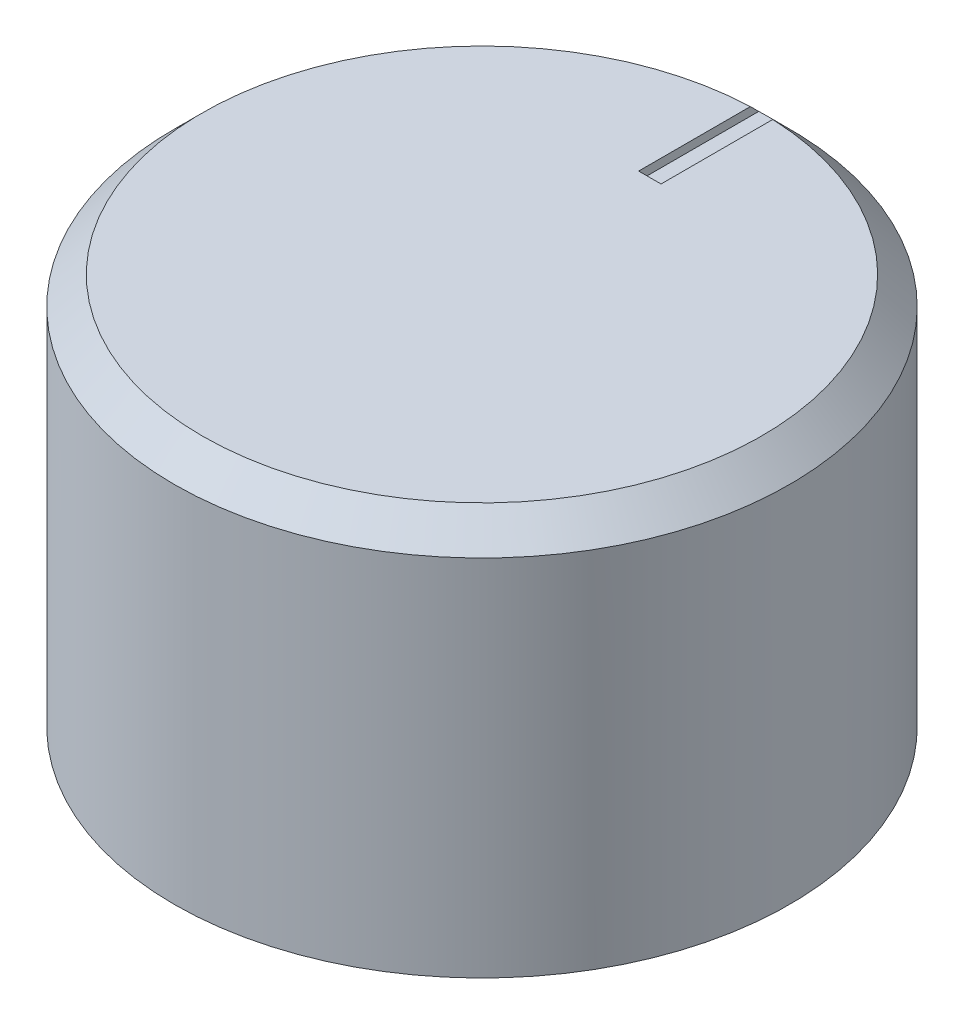
SolidWorks part; units mm, degrees
ref_plane "Front Plane" through (0, 0, 0) normal (0, 0, 1) x (1, 0, 0)
ref_plane "Top Plane" through (0, 0, 0) normal (0, 1, 0) x (1, 0, 0)
ref_plane "Right Plane" through (0, 0, 0) normal (1, 0, 0) x (0, 0, -1)
sketch "Sketch1" plane through (0, 0, 0) normal (0, 1, 0) x (1, 0, 0)
  circle A0 centre (0, 0) radius 11
  dimension "D1" = 22
extrude "Boss-Extrude1" add sketch "Sketch1" along normal blind 14
chamfer "Chamfer1" distance 1 angle 45 1 edges at (0, 14, 11)
sketch "Sketch3" plane through (0, 14, 0) normal (0, 1, 0) x (1, 0, 0)
  line L1 (-0.4, 6) -> (0.4, 6)
  line L2 (-0.4, 6) -> (-0.4, 11)
  line L3 (-0.4, 11) -> (0.4, 11)
  line L4 (0.4, 6) -> (0.4, 11)
  point P4 (0, 6)
  dimension "D1" = 0.8
  dimension "D2" = 6
  dimension "D3" = 5
extrude "Cut-Extrude1" cut sketch "Sketch3" against normal blind 0.3
sketch "Sketch4" plane through (0, 0, 0) normal (0, -1, 0) x (1, 0, 0)
  circle A0 centre (0, 0) radius 3
  dimension "D1" = 6
extrude "Cut-Extrude2" cut sketch "Sketch4" against normal blind 10
